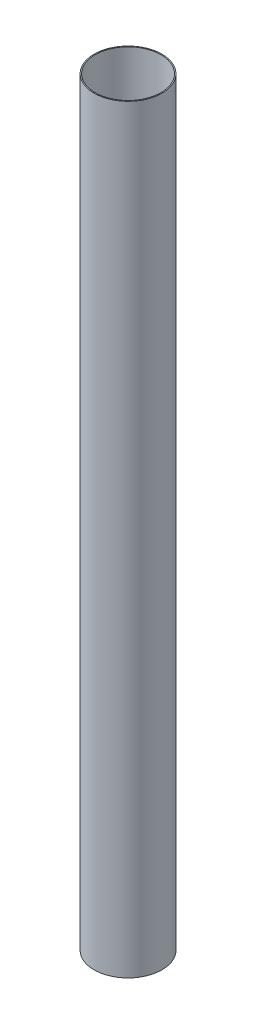
SolidWorks part; units mm, degrees
ref_plane "Front Plane" through (0, 0, 0) normal (1, 0, 0) x (0, 1, 0)
ref_plane "Top Plane" through (0, 0, 0) normal (0, 0, 1) x (0, 1, 0)
ref_plane "Right Plane" through (0, 0, 0) normal (0, 1, 0) x (-1, 0, 0)
sketch "Sketch2" plane through (0, 0, 0) normal (0, 0, 1) x (0, 1, 0)
  line L5 (635, 51.054) -> (1778, 51.054)
  line L6 (635, 51.054) -> (635, 49.53)
  line L7 (635, 49.53) -> (1778, 49.53)
  line L8 (1778, 51.054) -> (1778, 49.53)
  dimension "D1" = 1143
  dimension "D2" = 635
  dimension "D3" = 49.53
  dimension "D4" = 51.054
ref_axis "Axis1" through (0, -88.99, 0) along (0, 1, 0)
revolve "Revolve1" add sketch "Sketch2" angle 360 about axis through (0, -88.99, 0) along (0, 1, 0)
